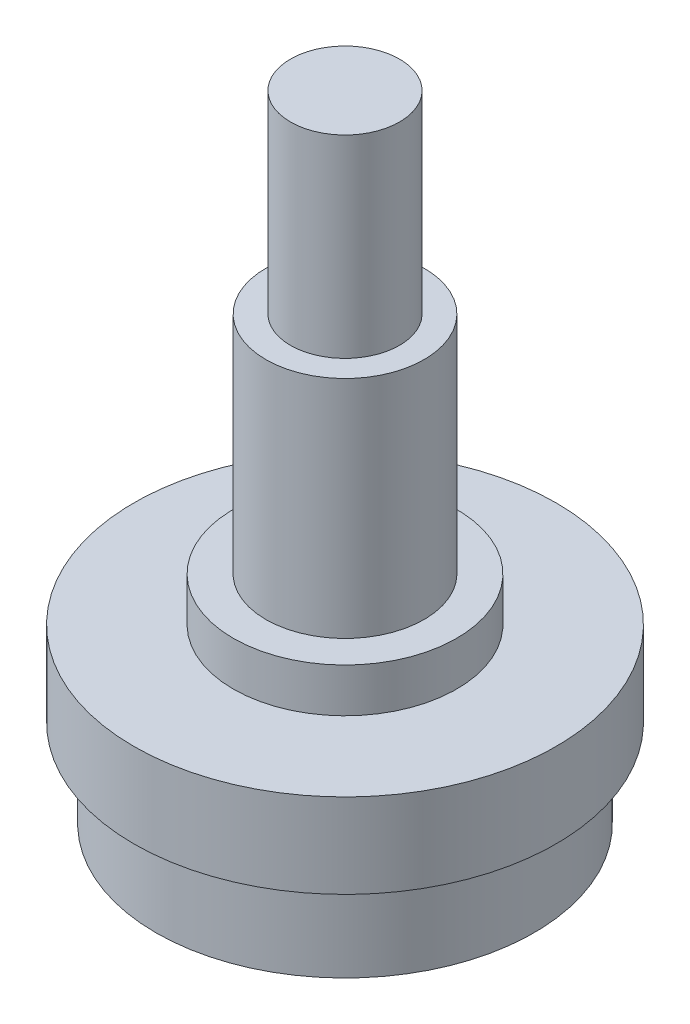
SolidWorks part; units mm, degrees
ref_plane "Front Plane" through (0, 0, 0) normal (0, 0, 1) x (1, 0, 0)
ref_plane "Top Plane" through (0, 0, 0) normal (0, 1, 0) x (1, 0, 0)
ref_plane "Right Plane" through (0, 0, 0) normal (1, 0, 0) x (0, 0, -1)
sketch "Sketch1" plane through (0, 0, 0) normal (0, 1, 0) x (1, 0, 0)
  circle A0 centre (0, 0) radius 10.75
  dimension "D1" = 21.5
extrude "Boss-Extrude1" add sketch "Sketch1" along normal blind 5
sketch "Sketch2" plane through (0, 5, 0) normal (0, 1, 0) x (1, 0, 0)
  circle A0 centre (0, 0) radius 12
  dimension "D1" = 24
extrude "Boss-Extrude2" add sketch "Sketch2" along normal blind 4.8
sketch "Sketch3" plane through (0, 9.8, 0) normal (0, 1, 0) x (1, 0, 0)
  circle A0 centre (0, 0) radius 6.35
  dimension "D1" = 12.7
extrude "Boss-Extrude3" add sketch "Sketch3" along normal blind 2.5
sketch "Sketch4" plane through (0, 12.3, 0) normal (0, 1, 0) x (1, 0, 0)
  circle A0 centre (0, 0) radius 4.5
  dimension "D1" = 9
extrude "Boss-Extrude4" add sketch "Sketch4" along normal blind 12.8
sketch "Sketch6" plane through (0, 25.1, 0) normal (0, 1, 0) x (1, 0, 0)
  circle A0 centre (0, 0) radius 3.1
  dimension "D1" = 6.2
extrude "Boss-Extrude5" add sketch "Sketch6" along normal blind 11
